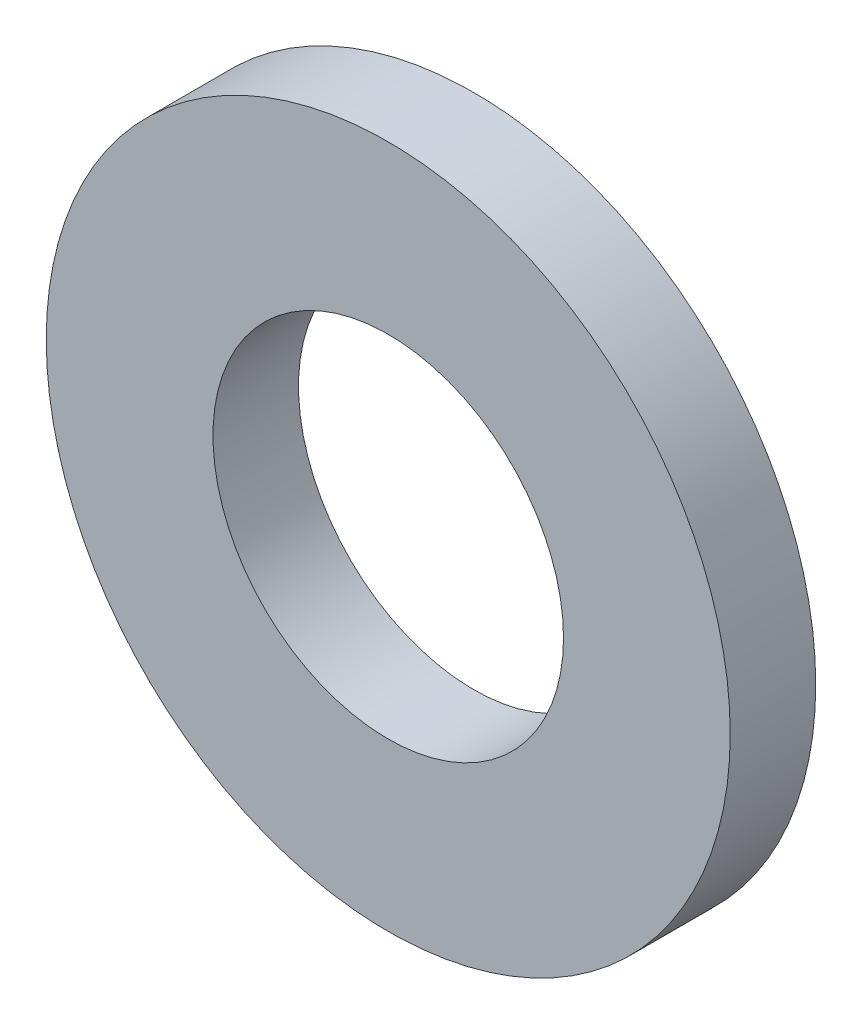
SolidWorks part; units mm, degrees
ref_plane "Front Plane" through (0, 0, 0) normal (0, 0, 1) x (1, 0, 0)
ref_plane "Top Plane" through (0, 0, 0) normal (0, 1, 0) x (1, 0, 0)
ref_plane "Right Plane" through (0, 0, 0) normal (1, 0, 0) x (0, 0, -1)
sketch "Sketch1" plane through (0, 0, 0) normal (0, 0, 1) x (1, 0, 0)
  circle A0 centre (0, 0) radius 4
  dimension "D1" = 8
extrude "Boss-Extrude1" add sketch "Sketch1" along normal blind 1
sketch "Sketch2" plane through (0, 0, 1) normal (0, 0, 1) x (1, 0, 0)
  circle A0 centre (0, 0) radius 2.05
  dimension "D1" = 4.1
extrude "Cut-Extrude1" cut sketch "Sketch2" against normal through all
